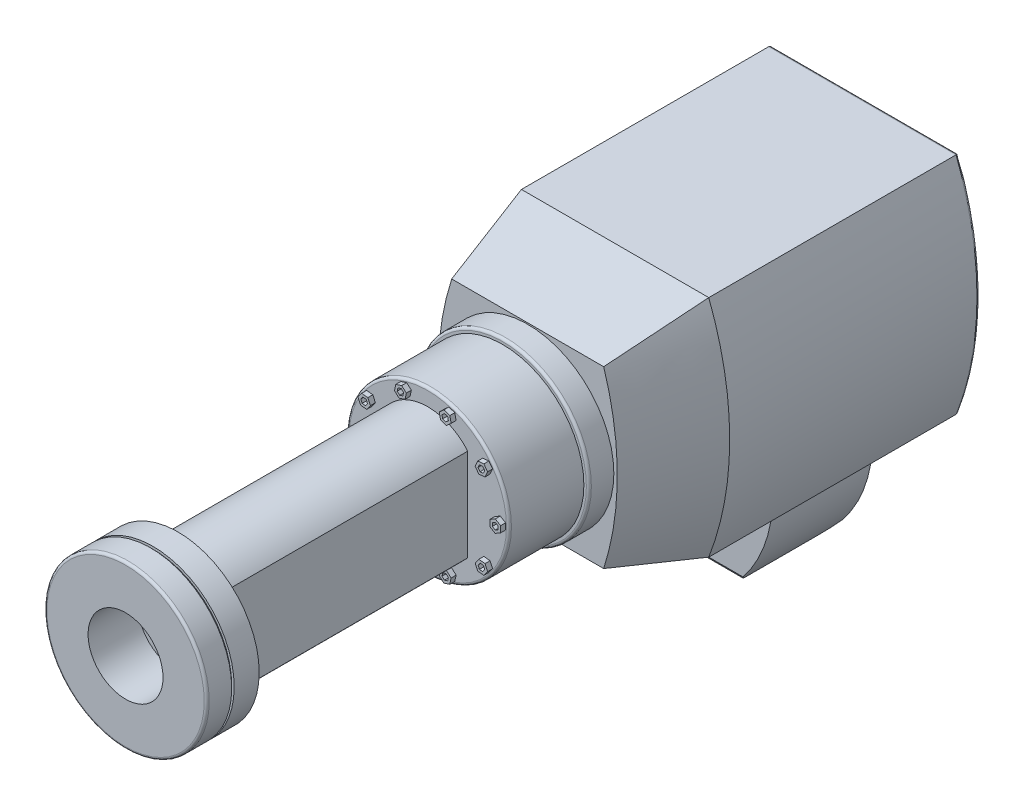
SolidWorks part; units mm, degrees
ref_plane "Front Plane" through (0, 0, 0) normal (0, 0, 1) x (1, 0, 0)
ref_plane "Top Plane" through (0, 0, 0) normal (0, 1, 0) x (1, 0, 0)
ref_plane "Right Plane" through (0, 0, 0) normal (1, 0, 0) x (0, 0, -1)
sketch "Sketch1" plane through (0, 0, 0) normal (0, 0, 1) x (1, 0, 0)
  line L0 (0, -45) -> (0, 45) construction
  line L1 (-37.5, 45) -> (37.5, 45)
  line L2 (-37.5, -45) -> (37.5, -45)
  arc A0 (-37.5, 45) -> (-37.5, -45) centre (79.119, 0) ccw
  arc A1 (37.5, 45) -> (37.5, -45) centre (-79.119, 0) cw
  point P4 (0, 0)
  point P8 (0, 45)
  point P11 (0, -45)
  dimension "D3" = 125
  dimension "D1" = 75
  dimension "D2" = 90
extrude "Boss-Extrude1" add sketch "Sketch1" along normal blind 100
sketch "Sketch2" plane through (0, 0, 100) normal (0, 0, 1) x (1, 0, 0)
  line L2 (37.5, 45) -> (-37.5, 45)
  line L3 (-37.5, -45) -> (37.5, -45)
  line L4 (37.5, 45) -> (-37.5, 45)
  line L5 (-37.5, -45) -> (37.5, -45)
  arc A2 (37.5, -45) -> (37.5, 45) centre (-79.119, 0) ccw
  arc A3 (-37.5, 45) -> (-37.5, -45) centre (79.119, 0) ccw
  arc A4 (37.5, -45) -> (37.5, 45) centre (-79.119, 0) ccw
  arc A5 (-37.5, 45) -> (-37.5, -45) centre (79.119, 0) ccw
  dimension "D1" = 0
ref_plane "Plane1" through (0, 0, 135) normal (0, 0, 1) x (1, 0, 0)
sketch "Sketch3" plane through (0, 0, 135) normal (0, 0, 1) x (1, 0, 0)
  line L4 (30.4255, 35) -> (-30.4255, 35)
  line L5 (-30.4255, -35) -> (30.4255, -35)
  line L6 (30.4255, 35) -> (-30.4255, 35)
  line L7 (-30.4255, -35) -> (30.4255, -35)
  arc A4 (30.4255, -35) -> (30.4255, 35) centre (-79.119, 0) ccw
  arc A5 (-30.4255, 35) -> (-30.4255, -35) centre (79.119, 0) ccw
  arc A6 (30.4255, -35) -> (30.4255, 35) centre (-79.119, 0) ccw
  arc A7 (-30.4255, 35) -> (-30.4255, -35) centre (79.119, 0) ccw
  dimension "D1" = 10
loft "Loft1" add profiles "Sketch3" section face at (0, 0, 100) section "Sketch3"
sketch "Sketch4" plane through (0, 0, 135) normal (0, 0, 1) x (1, 0, 0)
  circle A0 centre (0, 0) radius 34.5
  dimension "D1" = 69
extrude "Boss-Extrude2" add sketch "Sketch4" along normal blind 10
sketch "Sketch5" plane through (0, 0, 145) normal (0, 0, 1) x (1, 0, 0)
  circle A2 centre (0, 0) radius 32.5
  circle A3 centre (0, 0) radius 32.5
  dimension "D1" = 2
extrude "Boss-Extrude3" add sketch "Sketch5" along normal blind 30
sketch "Sketch6" plane through (0, 0, 175) normal (0, 0, 1) x (1, 0, 0)
  line L0 (0, 0) -> (29, 0) construction
  line L1 (29, 1.3453) -> (27.8349, 0.6726)
  line L2 (29, 2.5) -> (26.8349, 1.25)
  line L3 (26.8349, 1.25) -> (26.8349, -1.25)
  line L4 (26.8349, -1.25) -> (29, -2.5)
  line L5 (29, -2.5) -> (31.1651, -1.25)
  line L6 (31.1651, -1.25) -> (31.1651, 1.25)
  line L7 (31.1651, 1.25) -> (29, 2.5)
  line L8 (27.8349, 0.6726) -> (27.8349, -0.6726)
  line L9 (27.8349, -0.6726) -> (29, -1.3453)
  line L10 (29, -1.3453) -> (30.1651, -0.6726)
  line L11 (30.1651, -0.6726) -> (30.1651, 0.6726)
  line L12 (30.1651, 0.6726) -> (29, 1.3453)
  circle A0 centre (29, 0) radius 2.1651 construction
  dimension "D1" = 5
  dimension "D2" = 1
extrude "Boss-Extrude4" add sketch "Sketch6" along normal blind 2
pattern_circular "CirPattern1" count 10 over 360 about axis through (0, 0, 0) along (0, 0, 1) of "Boss-Extrude4"
sketch "Sketch7" plane through (0, 0, 175) normal (0, 0, 1) x (1, 0, 0)
  line L0 (0, 15.6585) -> (0, -12.1369) construction
  line L1 (0, 0) -> (16, 0) construction
  line L2 (16, -18.5) -> (16, 18.5)
  line L3 (-16, -18.5) -> (-16, 18.5)
  arc A0 (-16, 18.5) -> (16, 18.5) centre (0, 4.8985) cw
  arc A1 (-16, -18.5) -> (16, -18.5) centre (0, -4.8985) ccw
  point P8 (16, 0)
  dimension "D3" = 21
  dimension "D1" = 37
  dimension "D2" = 16
extrude "Boss-Extrude5" add sketch "Sketch7" along normal blind 100
sketch "Sketch8" plane through (0, 0, 275) normal (0, 0, 1) x (1, 0, 0)
  circle A2 centre (0, 0) radius 32.5
  circle A3 centre (0, 0) radius 32.5
  dimension "D1" = 0
extrude "Boss-Extrude6" add sketch "Sketch8" along normal blind 10
sketch "Sketch9" plane through (0, 0, 285) normal (0, 0, 1) x (1, 0, 0)
  circle A2 centre (0, 0) radius 31.5
  circle A3 centre (0, 0) radius 31.5
  dimension "D1" = 1
extrude "Boss-Extrude7" add sketch "Sketch9" along normal blind 1
sketch "Sketch10" plane through (0, 0, 286) normal (0, 0, 1) x (1, 0, 0)
  circle A2 centre (0, 0) radius 32.5
  circle A3 centre (0, 0) radius 32.5
  dimension "D1" = 0
extrude "Boss-Extrude8" add sketch "Sketch10" along normal blind 10
ref_plane "Plane2" through (-37.5, 0, 0) normal (1, 0, 0) x (0, 0, -1)
sketch "Sketch11" plane through (-37.5, 0, 0) normal (1, 0, 0) x (0, 0, -1)
  line L0 (-100, -45) -> (0, -45) construction
  circle A0 centre (-50, -45) radius 42.5
  dimension "D1" = 85
extrude "Boss-Extrude9" add sketch "Sketch11" along normal mid plane 21
sketch "Sketch12" plane through (-27, 0, 0) normal (1, 0, 0) x (0, 0, -1)
  line L0 (-50, -45) -> (-50, -75) construction
  line L1 (-100, -45) -> (0, -45) construction
  line L2 (-70, -45) -> (-70, -75)
  line L3 (-30, -45) -> (-30, -75)
  line L4 (-70, -45) -> (-30, -45)
  line L5 (-92.5, -45) -> (-7.5, -45) construction
  arc A0 (-70, -75) -> (-30, -75) centre (-50, -60.3189) ccw
  dimension "D4" = 24.81
  dimension "D1" = 30
  dimension "D2" = 20
  dimension "D3" = 20
extrude "Boss-Extrude10" add sketch "Sketch12" along normal blind 35
ref_plane "Plane3" through (0, 0, 50) normal (0, 0, 1) x (1, 0, 0)
sketch "Sketch13" plane through (0, 0, 50) normal (0, 0, 1) x (1, 0, 0)
  line L0 (8, -87) -> (8, -45)
  line L1 (8, -45) -> (33, -45)
  line L2 (-37.5, -45) -> (37.5, -45) construction
  arc A0 (8, -87) -> (33, -45) centre (-21.8393, -40.7981) ccw
  dimension "D3" = 55
  dimension "D1" = 25
  dimension "D2" = 42
extrude "Boss-Extrude11" add sketch "Sketch13" along normal mid plane 40
sketch "Sketch14" plane through (8, 0, 0) normal (-1, 0, 0) x (0, 0, 1)
  line L3 (70, -87) -> (70, -75)
  line L4 (30, -75) -> (30, -87)
  line L5 (30, -87) -> (70, -87)
  line L6 (70, -87) -> (70, -75)
  line L7 (30, -75) -> (30, -87)
  line L8 (30, -87) -> (70, -87)
  arc A1 (30, -75) -> (70, -75) centre (50, -60.3189) ccw
  arc A2 (30, -75) -> (70, -75) centre (50, -60.3189) ccw
  dimension "D1" = 0
extrude "Cut-Extrude1" cut sketch "Sketch14" against normal through all contours A2 L6 L8 L7
fillet "Fillet1" radius 1 9 edges at (32.5, 0, 296) (0, 45, 0) (-45.881, 0, 0) (0, -45, 0) (45.881, 0, 0) (32.5, 0, 175) (34.5, 0, 145) (-48, -45, 7.5) (-27, -87.5, 50)
sketch "Sketch15" plane through (0, 0, 296) normal (0, 0, 1) x (1, 0, 0)
  circle A0 centre (0, 0) radius 15
  dimension "D1" = 30
extrude "Cut-Extrude3" cut sketch "Sketch15" against normal blind 20
sketch "Sketch17" plane through (-48, 0, 0) normal (-1, 0, 0) x (0, 0, 1)
  circle A1 centre (50, -45) radius 15
  circle A2 centre (50, -45) radius 41.5
  circle A3 centre (50, -45) radius 41.5
  dimension "D1" = 0
extrude "Cut-Extrude5" cut sketch "Sketch17" against normal blind 20 contours A1
